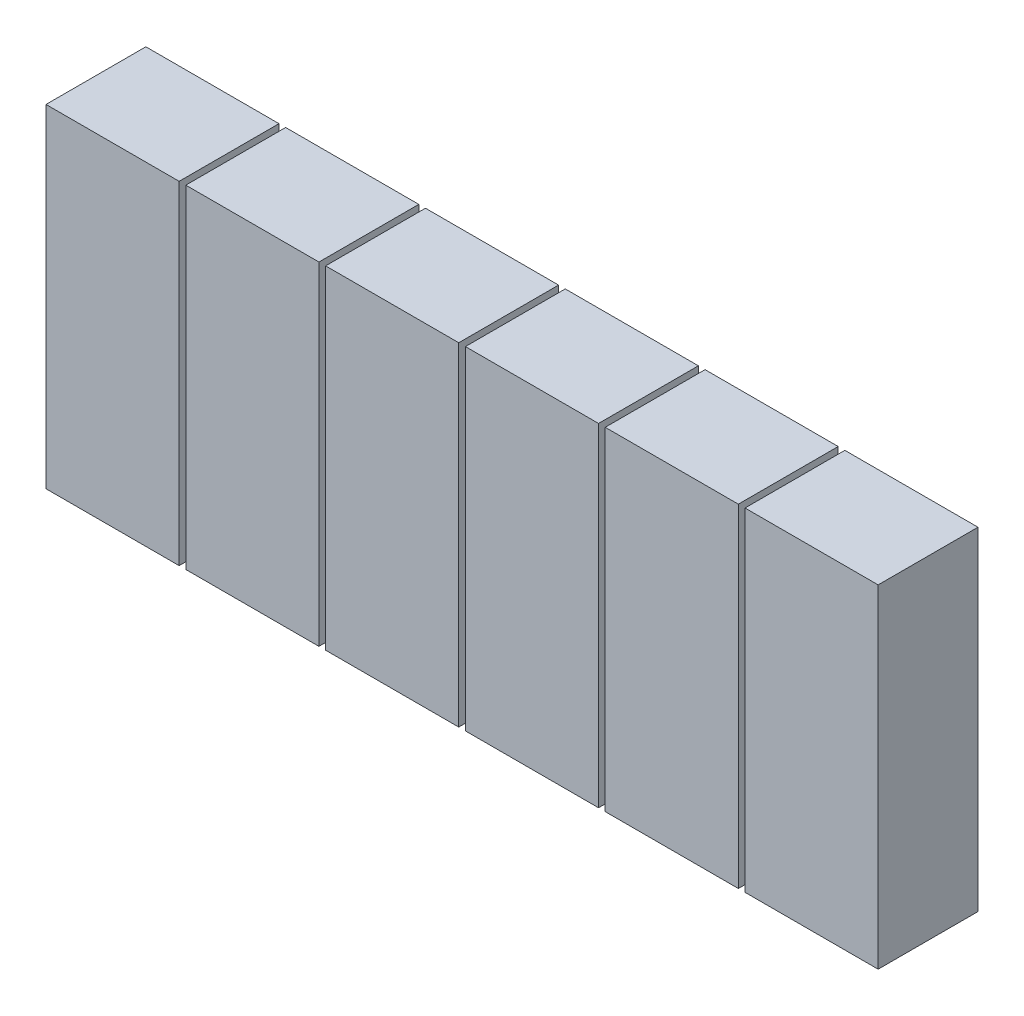
SolidWorks part; units mm, degrees
ref_plane "Front Plane" through (0, 0, 0) normal (0, 0, 1) x (1, 0, 0)
ref_plane "Top Plane" through (0, 0, 0) normal (0, 1, 0) x (1, 0, 0)
ref_plane "Right Plane" through (0, 0, 0) normal (1, 0, 0) x (0, 0, -1)
sketch "Sketch2" plane through (0, 0, 0) normal (0, 0, 1) x (1, 0, 0)
  line L0 (1100, 2500) -> (1100, -2500)
  line L1 (-1000, 2500) -> (1000, 2500)
  line L2 (-1000, 2500) -> (-1000, -2500)
  line L3 (-1000, -2500) -> (1000, -2500)
  line L4 (1000, 2500) -> (1000, -2500)
  line L5 (-1000, 2500) -> (1000, -2500) construction
  line L6 (-1000, -2500) -> (1000, 2500) construction
  line L7 (1100, 2500) -> (3100, 2500)
  line L8 (3100, 2500) -> (3100, -2500)
  line L9 (1100, -2500) -> (3100, -2500)
  line L10 (3200, 2500) -> (3200, -2500)
  line L11 (3200, 2500) -> (5200, 2500)
  line L12 (5200, 2500) -> (5200, -2500)
  line L13 (3200, -2500) -> (5200, -2500)
  line L14 (5300, 2500) -> (5300, -2500)
  line L15 (5300, 2500) -> (7300, 2500)
  line L16 (7300, 2500) -> (7300, -2500)
  line L17 (5300, -2500) -> (7300, -2500)
  line L18 (7400, 2500) -> (7400, -2500)
  line L19 (7400, 2500) -> (9400, 2500)
  line L20 (9400, 2500) -> (9400, -2500)
  line L21 (7400, -2500) -> (9400, -2500)
  line L22 (9500, 2500) -> (9500, -2500)
  line L23 (9500, 2500) -> (11500, 2500)
  line L24 (11500, 2500) -> (11500, -2500)
  line L25 (9500, -2500) -> (11500, -2500)
  point P0 (0, 0)
  dimension "D1" = 2000
  dimension "D2" = 5000
  dimension "D3" = 6
extrude "Boss-Extrude1" add sketch "Sketch2" along normal blind 1500
